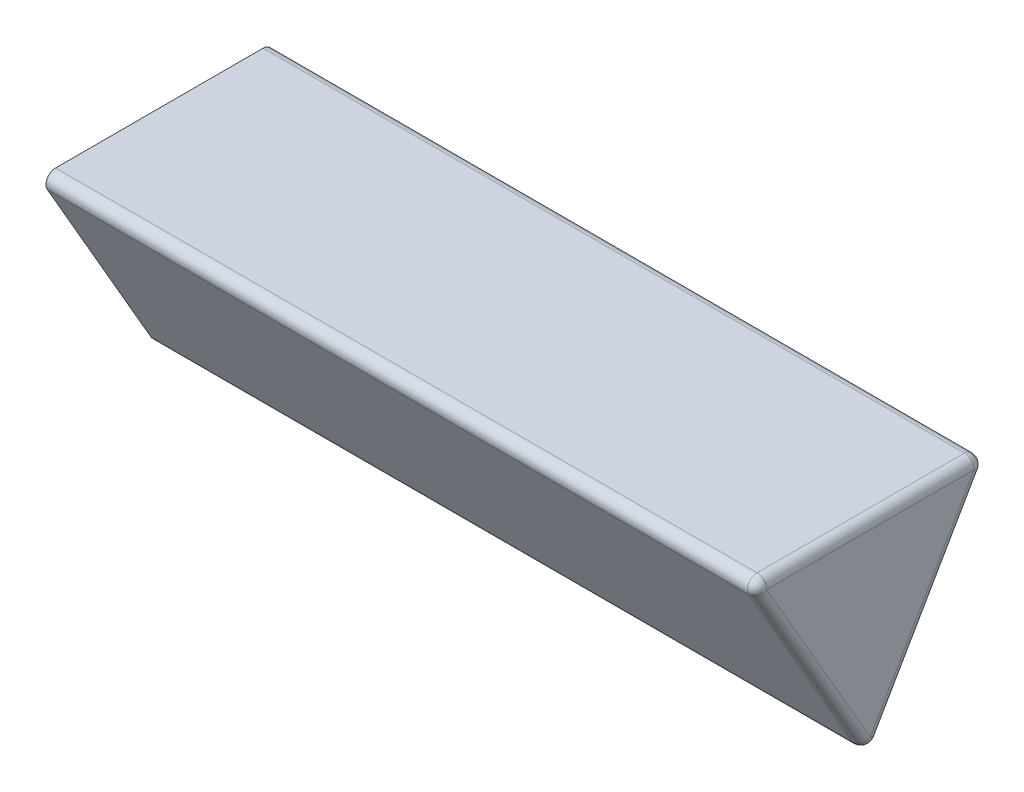
SolidWorks part; units mm, degrees
material "1060 Alloy"
ref_plane "Front Plane" through (0, 0, 0) normal (0, 0, 1) x (1, 0, 0)
ref_plane "Top Plane" through (0, 0, 0) normal (0, 1, 0) x (1, 0, 0)
ref_plane "Right Plane" through (0, 0, 0) normal (1, 0, 0) x (0, 0, -1)
sketch "Sketch2" plane through (0, 0, 0) normal (1, 0, 0) x (0, 0, -1)
  line L7 (31.75, 18.3309) -> (-31.75, 18.3309)
  line L8 (-31.75, 18.3309) -> (0, -36.6617)
  line L9 (0, -36.6617) -> (31.75, 18.3309)
  circle A0 centre (0, 0) radius 36.6617 construction
  dimension "D1" = 63.5
extrude "Boss-Extrude2" add sketch "Sketch2" along normal blind 187.452
sketch "Sketch3" plane through (0, 0, 0) normal (1, 0, 0) x (0, 0, -1)
  line L1 (30.1625, 17.4143) -> (-30.1625, 17.4143)
  line L2 (-30.1625, 17.4143) -> (0, -34.8287)
  line L3 (0, -34.8287) -> (30.1625, 17.4143)
  circle A0 centre (0, 0) radius 34.8287 construction
  dimension "D1" = 60.325
extrude "Cut-Extrude1" cut sketch "Sketch3" along normal blind 186.182
fillet "Fillet1" radius 2.54 6 edges at (93.091, 17.4143, -30.1625) (93.726, 18.3309, -31.75) (93.091, -34.8287, 0) (93.726, -36.6617, 0) (93.091, 17.4143, 30.1625) (93.726, 18.3309, 31.75)
fillet "Fillet2" radius 2.54 12 edges at (186.182, 16.1443, -27.9628) (186.182, -8.7072, -15.0813) (186.182, -32.2887, 0) (186.182, -8.7072, 15.0812) (186.182, 16.1443, 27.9628) (187.452, -9.1654, -15.875) (187.452, -34.1217, 0) (187.452, -9.1654, 15.875) (187.452, 17.0609, 29.5503) (187.452, 18.3309, 0) (186.182, 17.4143, 0) (187.452, 17.0609, -29.5503)
